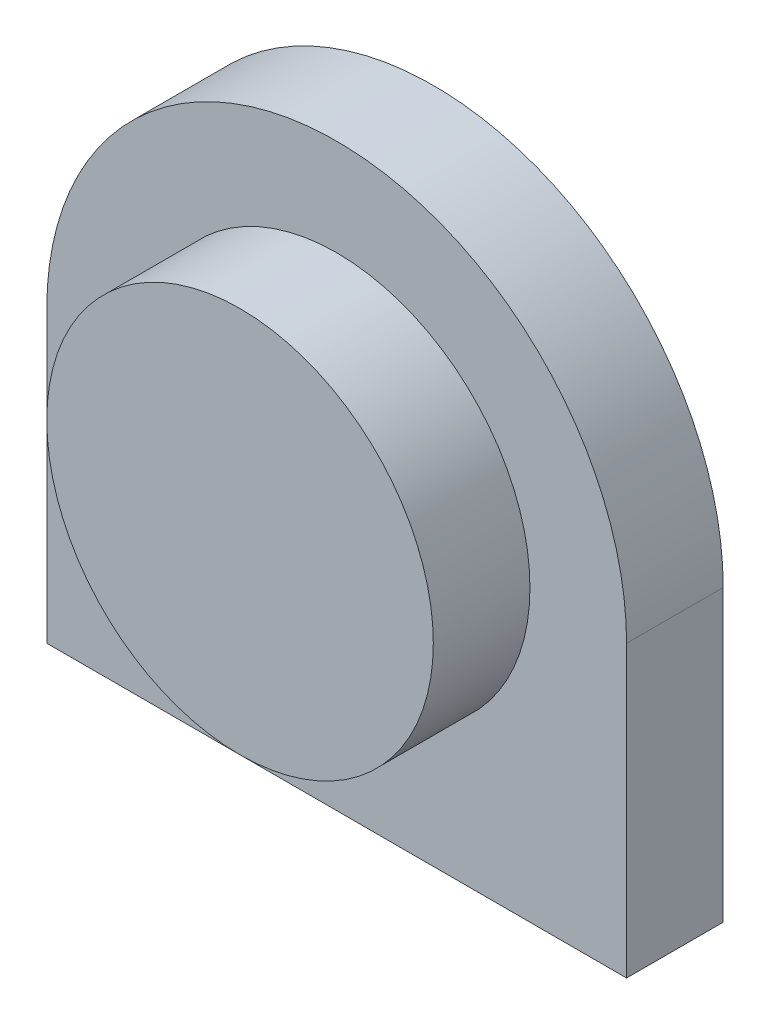
SolidWorks part; units mm, degrees
ref_plane "Front" through (0, 0, 0) normal (0, 0, 1) x (1, 0, 0)
ref_plane "Top" through (0, 0, 0) normal (0, 1, 0) x (1, 0, 0)
ref_plane "Right" through (0, 0, 0) normal (1, 0, 0) x (0, 0, -1)
sketch "草图1" plane through (0, 0, 0) normal (0, 0, 1) x (1, 0, 0)
  line L2 (-30, 0) -> (-30, -30)
  line L3 (-30, -30) -> (30, -30)
  line L4 (30, 0) -> (30, -30)
  arc A0 (30, 0) -> (-30, 0) centre (0, 0) ccw
extrude "凸台-拉伸1" add sketch "草图1" along normal blind 10
sketch "草图2" plane through (0, 0, 10) normal (0, 0, 1) x (1, 0, 0)
  circle A0 centre (0, 0) radius 20
extrude "凸台-拉伸2" add sketch "草图2" along normal blind 10
